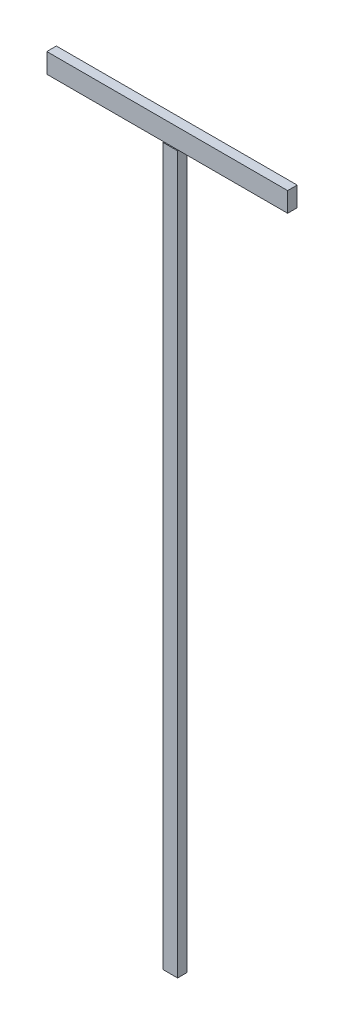
SolidWorks part; units mm, degrees
ref_plane "Спереди" through (0, 0, 0) normal (0, 0, 1) x (1, 0, 0)
ref_plane "Сверху" through (0, 0, 0) normal (0, 1, 0) x (1, 0, 0)
ref_plane "Справа" through (0, 0, 0) normal (1, 0, 0) x (0, 0, -1)
sketch "Эскиз1" plane through (0, 0, 0) normal (0, 0, 1) x (1, 0, 0)
  line L1 (-69.743, 26.4919) -> (182.2935, 26.4919)
  line L2 (-69.743, 26.4919) -> (-69.743, 47.082)
  line L3 (-69.743, 47.082) -> (182.2935, 47.082)
  line L4 (182.2935, 26.4919) -> (182.2935, 47.082)
  line L5 (51.7854, 25.5049) -> (67.133, 25.5049)
  line L6 (51.7854, 25.5049) -> (51.7854, -724.0367)
  line L7 (51.7854, -724.0367) -> (67.133, -724.0367)
  line L8 (67.133, 25.5049) -> (67.133, -724.0367)
extrude "Бобышка-Вытянуть1" add sketch "Эскиз1" along normal blind 10 contours L1 L4 L3 L2 | L6 L5 L8 L7
